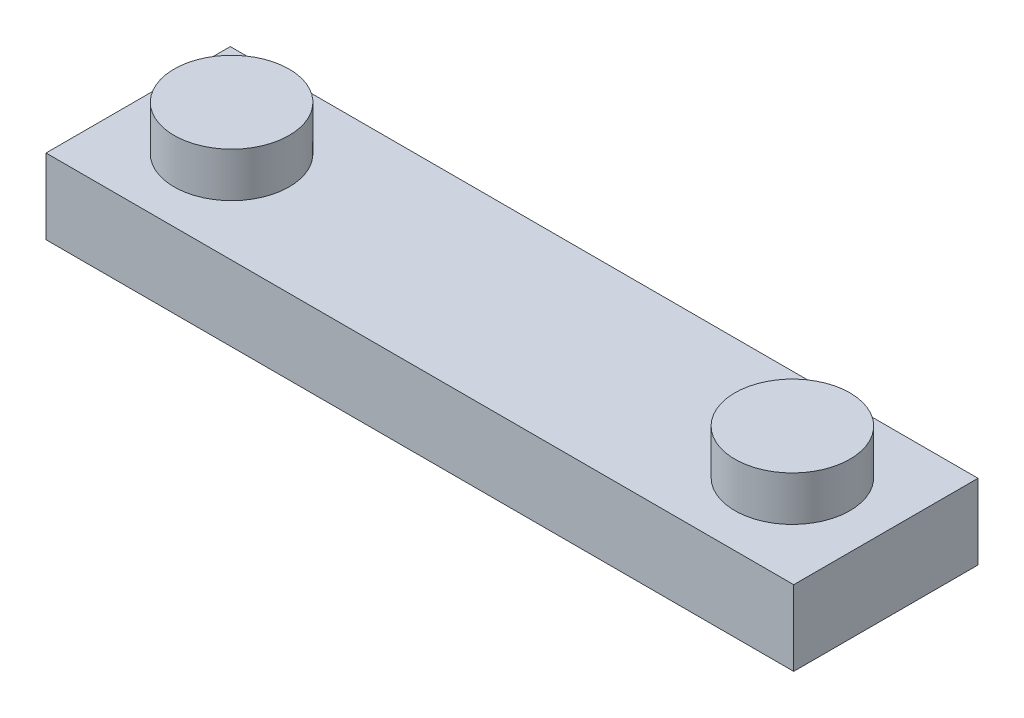
SolidWorks part; units mm, degrees
ref_plane "Front Plane" through (0, 0, 0) normal (0, 0, 1) x (1, 0, 0)
ref_plane "Top Plane" through (0, 0, 0) normal (0, 1, 0) x (1, 0, 0)
ref_plane "Right Plane" through (0, 0, 0) normal (1, 0, 0) x (0, 0, -1)
sketch "Sketch1" plane through (0, 0, 0) normal (0, 1, 0) x (1, 0, 0)
  line L1 (-15.925, 3.925) -> (15.925, 3.925)
  line L2 (-15.925, 3.925) -> (-15.925, -3.925)
  line L3 (-15.925, -3.925) -> (15.925, -3.925)
  line L4 (15.925, 3.925) -> (15.925, -3.925)
  line L5 (-15.925, 3.925) -> (15.925, -3.925) construction
  line L6 (-15.925, -3.925) -> (15.925, 3.925) construction
  point P0 (0, 0)
  dimension "D1" = 31.85
  dimension "D2" = 7.85
extrude "Boss-Extrude1" add sketch "Sketch1" against normal blind 3.2
sketch "Sketch2" plane through (0, 0, 0) normal (0, 1, 0) x (1, 0, 0)
  line L1 (-15.925, 3.925) -> (-15.925, -3.925) construction
  line L2 (15.925, -3.925) -> (15.925, 3.925) construction
  line L3 (15.925, 3.925) -> (-15.925, 3.925) construction
  circle A0 centre (11.9437, 0) radius 2.45
  circle A1 centre (-11.9438, 0) radius 2.45
  dimension "D1" = 4.9
  dimension "D2" = 4.9
  dimension "D3" = 3.9813
  dimension "D4" = 3.9813
  dimension "D5" = 3.925
  dimension "D6" = 3.925
extrude "Boss-Extrude2" add sketch "Sketch2" along normal blind 1.9
shell "Shell1" thickness 1.5
sketch "Sketch3" plane through (0, -1.5, 0) normal (0, -1, 0) x (1, 0, 0)
  line L1 (-15.925, -3.925) -> (-15.925, 3.925) construction
  line L2 (15.925, 3.925) -> (15.925, -3.925) construction
  line L3 (-15.925, 3.925) -> (15.925, 3.925) construction
  circle A0 centre (-7.9625, 0) radius 1.5
  circle A1 centre (-7.9625, 0) radius 0.53
  circle A2 centre (0, 0) radius 1.5
  circle A3 centre (0, 0) radius 0.53
  circle A4 centre (7.9625, 0) radius 1.5
  circle A5 centre (7.9625, 0) radius 0.53
  dimension "D1" = 3
  dimension "D2" = 1.06
  dimension "D3" = 7.9625
  dimension "D4" = 7.9625
  dimension "D5" = 3.925
  dimension "D6" = 3.925
extrude "Boss-Extrude3" add sketch "Sketch3" along normal offset from surface (1.5 mm away) 0.2 up to face at (0, -3.2, 0)
